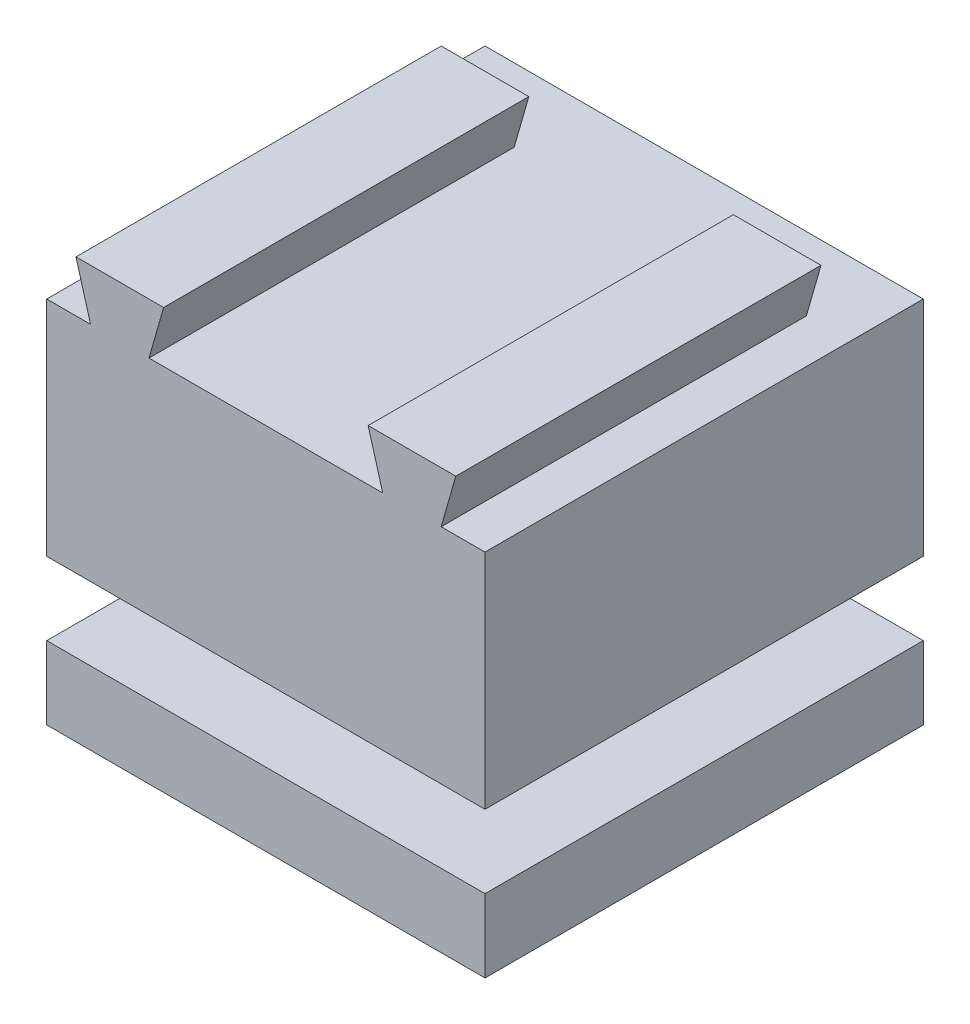
SolidWorks part; units mm, degrees
ref_plane "Alzado" through (0, 0, 0) normal (0, 0, 1) x (1, 0, 0)
ref_plane "Planta" through (0, 0, 0) normal (0, 1, 0) x (1, 0, 0)
ref_plane "Vista lateral" through (0, 0, 0) normal (1, 0, 0) x (0, 0, -1)
sketch "Croquis2" plane through (0, 0, 0) normal (0, 1, 0) x (1, 0, 0)
  line L0 (30, -30) -> (30, 30)
  line L1 (30, -30) -> (-30, -30)
  line L2 (30, 30) -> (-30, 30)
  line L3 (-30, -30) -> (-30, 30)
  line L4 (30, -30) -> (-30, 30) construction
  line L5 (30, 30) -> (-30, -30) construction
  point P1 (0, 0)
  dimension "D1" = 60
  dimension "D2" = 60
extrude "Saliente-Extruir1" add sketch "Croquis2" along normal blind 50.5
sketch "Croquis4" plane through (0, 0, 30) normal (0, 0, 1) x (1, 0, 0)
  line L0 (-26, 57.5) -> (-14, 57.5)
  line L1 (-24, 50.5) -> (-16, 50.5)
  line L2 (-16, 50.5) -> (-14, 57.5)
  line L3 (-30, 0) -> (30, 0) construction
  line L4 (-20, 50.5) -> (-20, 57.5) construction
  line L5 (-30, 50.5) -> (-30, 0) construction
  line L6 (-26, 57.5) -> (-24, 50.5)
  dimension "D8" = 12
  dimension "D1" = 7
  dimension "D2" = 8
  dimension "D4" = 6
  dimension "D5" = 4
  dimension "D6" = 50.5
  dimension "D3" = 10
extrude "Saliente-Extruir3" add sketch "Croquis4" against normal blind 50 contours L0 L2 L1 L6
pattern_linear "MatrizL2" count 2 spacing 40 along (1, 0, 0) of "Saliente-Extruir3"
sketch "Croquis5" plane through (0, 0, 30) normal (0, 0, 1) x (1, 0, 0)
  line L0 (-30, 20) -> (-20, 20)
  line L1 (-20, 20) -> (-20, 10)
  line L2 (-30, 10) -> (-20, 10)
  line L3 (-30, 20) -> (-30, 10)
  dimension "D2" = 10
  dimension "D3" = 10
  dimension "D1" = 10
extrude "Cortar-Extruir1" cut sketch "Croquis5" against normal through all
pattern_linear "MatrizL3" count 2 spacing 50 along (1, 0, 0) of "Cortar-Extruir1"
pattern_circular "MatrizC1" count 2 over 90 of "Cortar-Extruir1"
